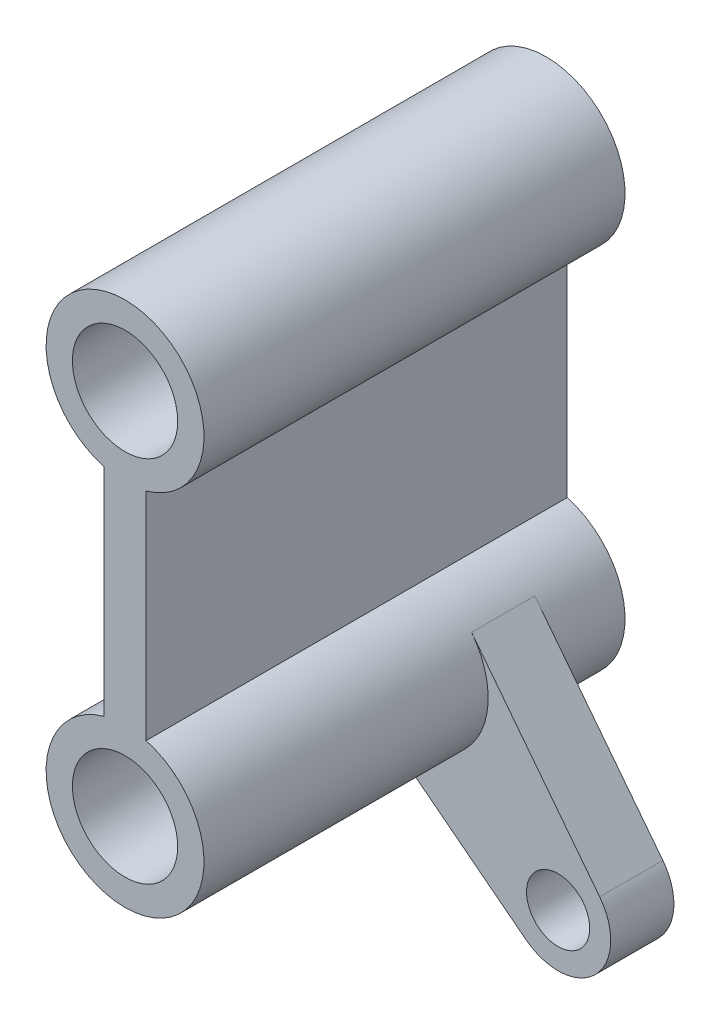
SolidWorks part; units mm, degrees
ref_plane "Спереди" through (0, 0, 0) normal (0, 0, 1) x (1, 0, 0)
ref_plane "Сверху" through (0, 0, 0) normal (0, 1, 0) x (1, 0, 0)
ref_plane "Справа" through (0, 0, 0) normal (1, 0, 0) x (0, 0, -1)
sketch "Эскиз1" plane through (0, 0, 0) normal (0, 0, 1) x (1, 0, 0)
  line L0 (0, 0) -> (0, 35) construction
  line L2 (-2, 5) -> (2, 5)
  line L3 (-2, 5) -> (-2, 30)
  line L4 (-2, 30) -> (2, 30)
  line L5 (2, 5) -> (2, 30)
  line L6 (-2, 5) -> (2, 30) construction
  line L7 (-2, 30) -> (2, 5) construction
  circle A0 centre (0, 0) radius 5
  circle A1 centre (0, 0) radius 7.5
  circle A2 centre (0, 35) radius 5
  circle A3 centre (0, 35) radius 7.5
  point P7 (0, 17.5)
  dimension "D1" = 10
  dimension "D2" = 15
  dimension "D3" = 15
  dimension "D4" = 35
  dimension "D5" = 4
extrude "Бобышка-Вытянуть1" add sketch "Эскиз1" along normal blind 40 contours L5 A3 L3 L4 A2 | L3 A3 L5 L4 | A3 L3 A1 L5 | L5 A1 L3 L2 | L3 A1 L5 L2 A0
ref_plane "Плоскость1" through (0, 0, 10) normal (0, 0, -1) x (-1, 0, 0)
sketch "Эскиз3" plane through (0, 0, 10) normal (0, 0, -1) x (-1, 0, 0)
  line L0 (0, 0) -> (-14.1421, -14.1421) construction
  line L1 (0, 0) -> (0, -7.5) construction
  line L2 (-18.0919, -11.0763) -> (-5.9246, 4.5988)
  line L3 (-11.0763, -18.0919) -> (4.5988, -5.9246)
  line L4 (0, 0) -> (-5.9246, 4.5988) construction
  line L5 (0, 0) -> (4.5988, -5.9246) construction
  line L6 (-5.9246, 4.5988) -> (-3.9497, 3.0659)
  line L7 (4.5988, -5.9246) -> (3.0659, -3.9497)
  circle A0 centre (-14.1421, -14.1421) radius 5
  arc A1 (-2, 7.2284) -> (2, 7.2284) centre (0, 0) ccw construction
  circle A2 centre (0, 0) radius 5 construction
  arc A3 (-3.9497, 3.0659) -> (3.0659, -3.9497) centre (0, 0) ccw
  dimension "D2" = 10
  dimension "D1" = 45
  dimension "D3" = 20
extrude "Бобышка-Вытянуть2" add sketch "Эскиз3" along normal mid plane 6 contours A3 L6 L2 A0 L3 L7 | A0
sketch "Эскиз4" plane through (0, 0, 13) normal (0, 0, 1) x (1, 0, 0)
  circle A0 centre (14.1421, -14.1421) radius 3
  dimension "D1" = 6
extrude "Вырез-Вытянуть2" cut sketch "Эскиз4" against normal through all
